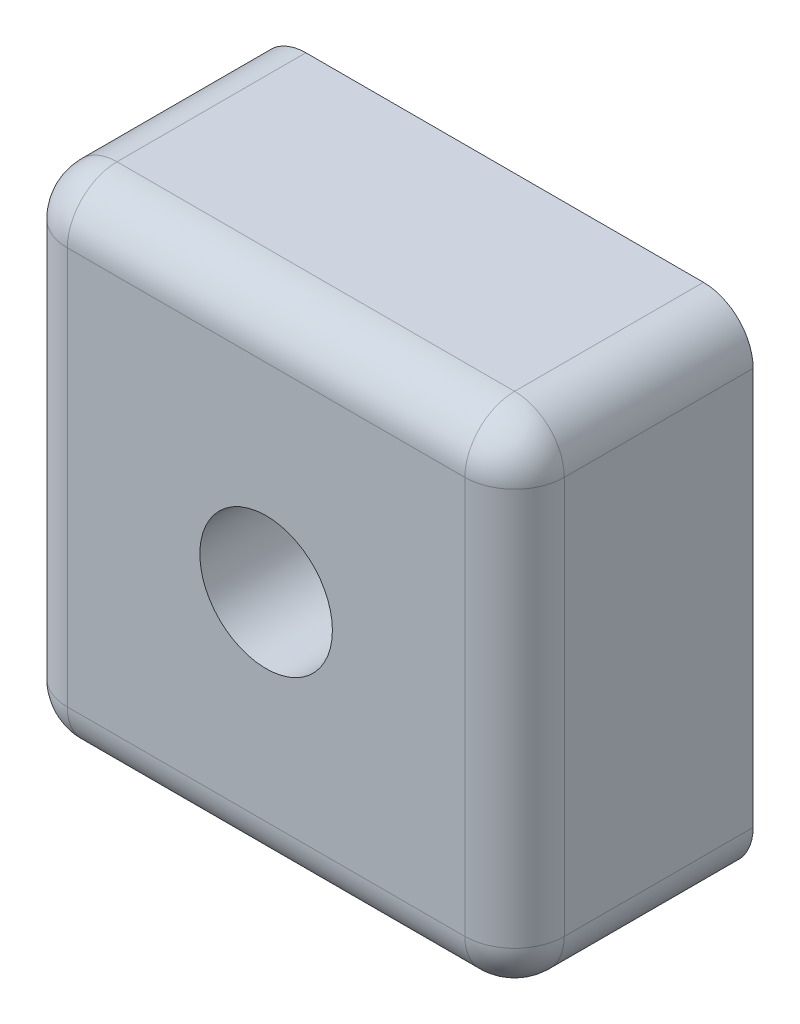
SolidWorks part; units mm, degrees
ref_plane "前视基准面" through (0, 0, 0) normal (0, 0, 1) x (1, 0, 0)
ref_plane "上视基准面" through (0, 0, 0) normal (0, 1, 0) x (1, 0, 0)
ref_plane "右视基准面" through (0, 0, 0) normal (1, 0, 0) x (0, 0, -1)
sketch "草图1" plane through (0, 0, 0) normal (0, 0, 1) x (1, 0, 0)
  line L0 (-50, -50) -> (50, -50)
  line L1 (0, 0) -> (50, 0)
  line L2 (0, -50) -> (0, 50)
  line L3 (-50, 50) -> (50, 50)
  line L4 (50, -50) -> (50, 50)
  line L5 (-50, -50) -> (-50, 50)
  circle A0 centre (0, 0) radius 13.3398
  circle A1 centre (0, 0) radius 20.9
  dimension "D1" = 50
  dimension "D2" = 50
extrude "凸台-拉伸1" add sketch "草图1" along normal blind 48 contours A1 L2 L3 L5 L0 | A1 L1 L4 L3 L2 | L1 A1 L2 A0 | L2 A1 A0 | L2 A1 L1 A0 | A1 L2 L0 L4 L1
fillet "圆角2" radius 10 4 edges at (-50, -50, 24) (50, -50, 24) (50, 50, 24) (-50, 50, 24)
fillet "圆角3" radius 10 8 edges at (-47.0711, 47.0711, 48) (-50, 0, 48) (-47.0711, -47.0711, 48) (0, -50, 48) (47.0711, -47.0711, 48) (50, 0, 48) (47.0711, 47.0711, 48) (0, 50, 48)
